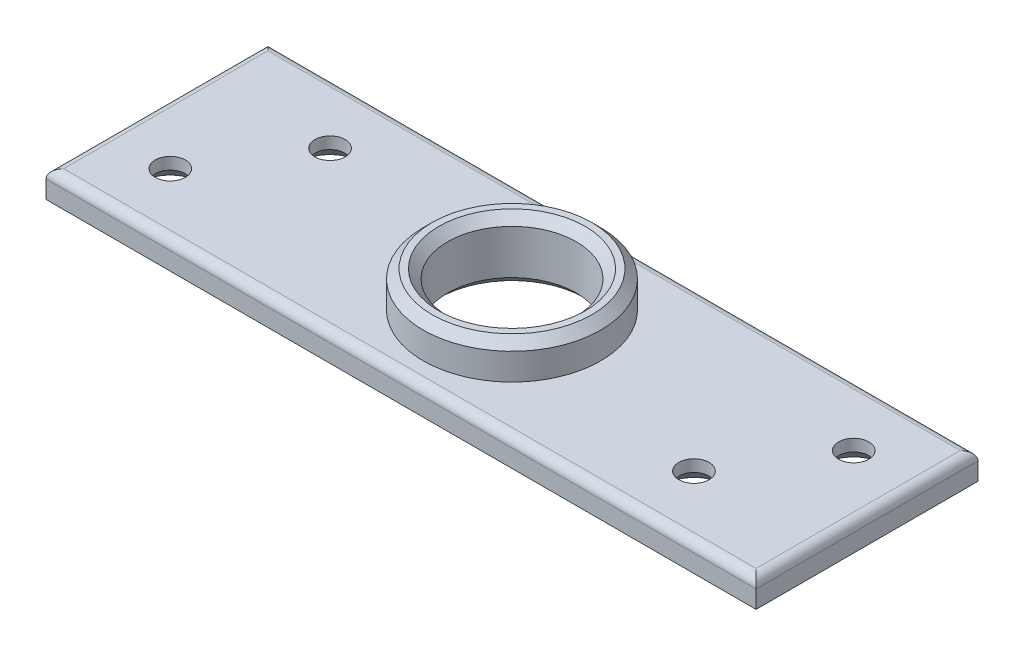
SolidWorks part; units mm, degrees
material "Aço cromo inoxidável"
ref_plane "Plano frontal" through (0, 0, 0) normal (0, 0, 1) x (1, 0, 0)
ref_plane "Plano superior" through (0, 0, 0) normal (0, 1, 0) x (1, 0, 0)
ref_plane "Plano direito" through (0, 0, 0) normal (1, 0, 0) x (0, 0, -1)
other "Caixa delimitadora"
ref_plane "Default Plane" through (-40, -1.5, 12.5) normal (0, 0, -1) x (-1, 0, 0)
sketch "Esboço1" plane through (0, 0, 0) normal (0, 1, 0) x (1, 0, 0)
  line L1 (-40, -12.5) -> (40, -12.5)
  line L2 (-40, -12.5) -> (-40, 12.5)
  line L3 (-40, 12.5) -> (40, 12.5)
  line L4 (40, -12.5) -> (40, 12.5)
  line L5 (-40, -12.5) -> (40, 12.5) construction
  line L6 (-40, 12.5) -> (40, -12.5) construction
  circle A0 centre (0, 0) radius 10
  point P0 (0, 0)
  dimension "D3" = 20
  dimension "D1" = 80
  dimension "D2" = 25
extrude "Ressalto-extrusão1" add sketch "Esboço1" along normal mid plane 3
sketch "Esboço2" plane through (0, -1.5, 0) normal (0, -1, 0) x (1, 0, 0)
  circle A0 centre (0, 0) radius 10 construction
  circle A1 centre (0, 0) radius 10
  circle A2 centre (0, 0) radius 7.25
  dimension "D1" = 2.75
extrude "Ressalto-extrusão2" add sketch "Esboço2" against normal offset from surface (7 mm away) 4 separate body up to face at (0, 1.5, 0) offset beyond the face yes
chamfer "Chanfro1" distance 1 angle 45 4 edges at (0, 5.5, -7.25) (0, 5.5, -10) (0, -1.5, -10) (0, -1.5, -7.25)
fillet "Filete1" radius 1 4 edges at (-40, 1.5, 0) (0, 1.5, -12.5) (40, 1.5, 0) (0, 1.5, 12.5)
sketch "Esboço3" plane through (0, -1.5, 0) normal (0, -1, 0) x (-1, 0, 0)
  point P0 (26, 5.5)
  point P1 (33, -5.5)
  point P3 (-26, -5.5)
  point P5 (-33, 5.5)
  dimension "D1" = 26
  dimension "D2" = 33
  dimension "D3" = 26
  dimension "D4" = 33
  dimension "D5" = 5.5
  dimension "D6" = 5.5
hole_wizard "Escareado para SFHCS M31" positions "Esboço4" profile "Esboço5" countersink size "M3" standard "Ansi Metric" end condition through all
sketch "Esboço4" plane through (0, -1.5, 0) normal (0, -1, 0) x (-1, 0, 0)
  point P0 (-33, 5.5)
  point P3 (-26, -5.5)
  point P6 (26, 5.5)
  point P9 (33, -5.5)
sketch "Esboço5" plane through (33, -1.5, -5.5) normal (1, 0, 0) x (0, 0, -1)
  line L0 (0, 0) -> (0, 7)
  line L1 (0, 7) -> (1.7, 7)
  line L2 (1.7, 7) -> (1.7, 1.66)
  line L3 (1.7, 1.66) -> (3.36, 0)
  line L5 (3.36, 0) -> (0, 0)
  line L6 (-1.7, 1.66) -> (-3.36, 0) construction
  line L11 (0, -6.35) -> (0, 107.95) construction
  dimension "Thru Hole Dia." = 3.4
  dimension "Thru Hole Depth" = 7
  dimension "Near C'Sink Dia." = 6.72
  dimension "Near C'Sink Angle" = 90
